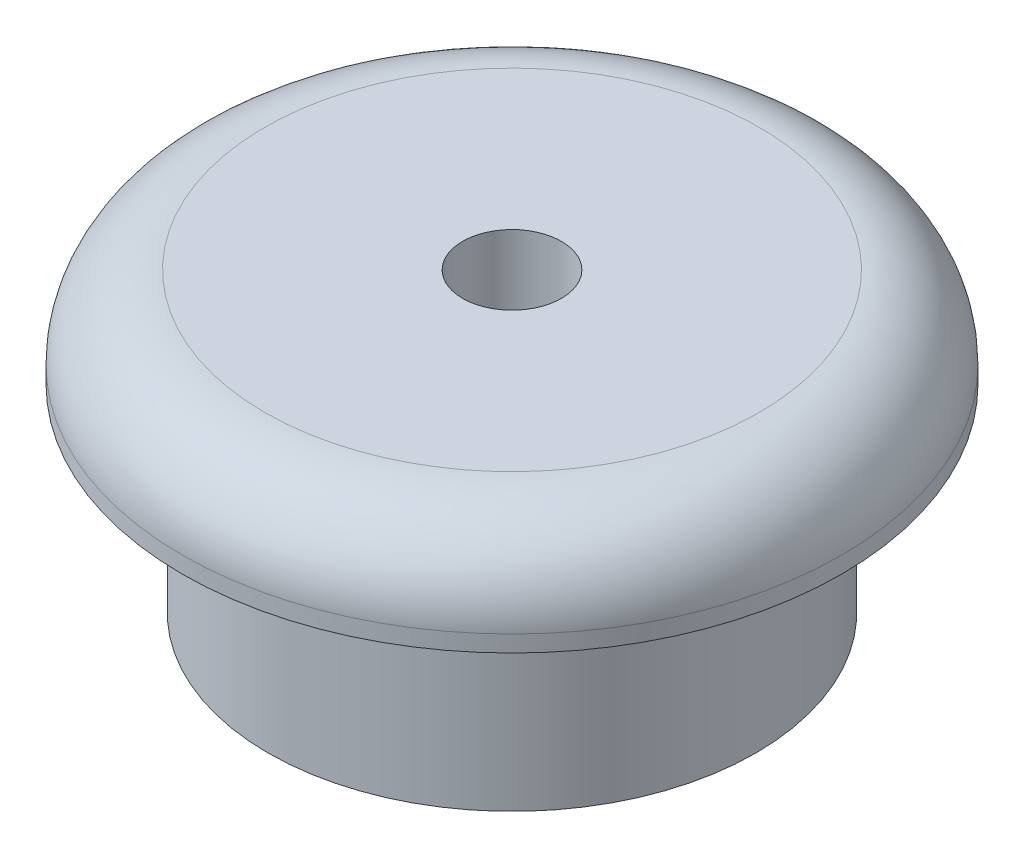
SolidWorks part; units mm, degrees
material "Custom Plastic"
ref_plane "Front Plane" through (0, 0, 0) normal (0, 0, 1) x (1, 0, 0)
ref_plane "Top Plane" through (0, 0, 0) normal (0, 1, 0) x (1, 0, 0)
ref_plane "Right Plane" through (0, 0, 0) normal (1, 0, 0) x (0, 0, -1)
sketch "Sketch1" plane through (0, 0, 0) normal (0, 1, 0) x (1, 0, 0)
  line L0 (2.2, 2.2194) -> (2.2, -2.2194)
  circle A0 centre (0, 0) radius 7.4
  arc A1 (2.2, 2.2194) -> (2.2, -2.2194) centre (0, 0) ccw
  dimension "D1" = 6.25
  dimension "D2" = 14.8
  dimension "D3" = 2.2
extrude "Boss-Extrude1" add sketch "Sketch1" along normal blind 6
sketch "Sketch2" plane through (0, 6, 0) normal (0, 1, 0) x (1, 0, 0)
  line L0 (2.2, -2.2194) -> (2.2, 2.2194) construction
  line L1 (2.2, -2.2194) -> (2.2, 2.2194)
  circle A0 centre (0, 0) radius 7.4 construction
  arc A1 (2.2, 2.2194) -> (2.2, -2.2194) centre (0, 0) ccw construction
  circle A2 centre (0, 0) radius 7.4
  arc A3 (2.2, 2.2194) -> (2.2, -2.2194) centre (0, 0) ccw
  circle A4 centre (0, 0) radius 10
  circle A5 centre (0, 0) radius 1.5
  dimension "D1" = 20
  dimension "D2" = 3
extrude "Boss-Extrude2" add sketch "Sketch2" along normal blind 3 contours A4 | A5
fillet "Fillet1" radius 2.5 1 edges at (0, 9, 10)
